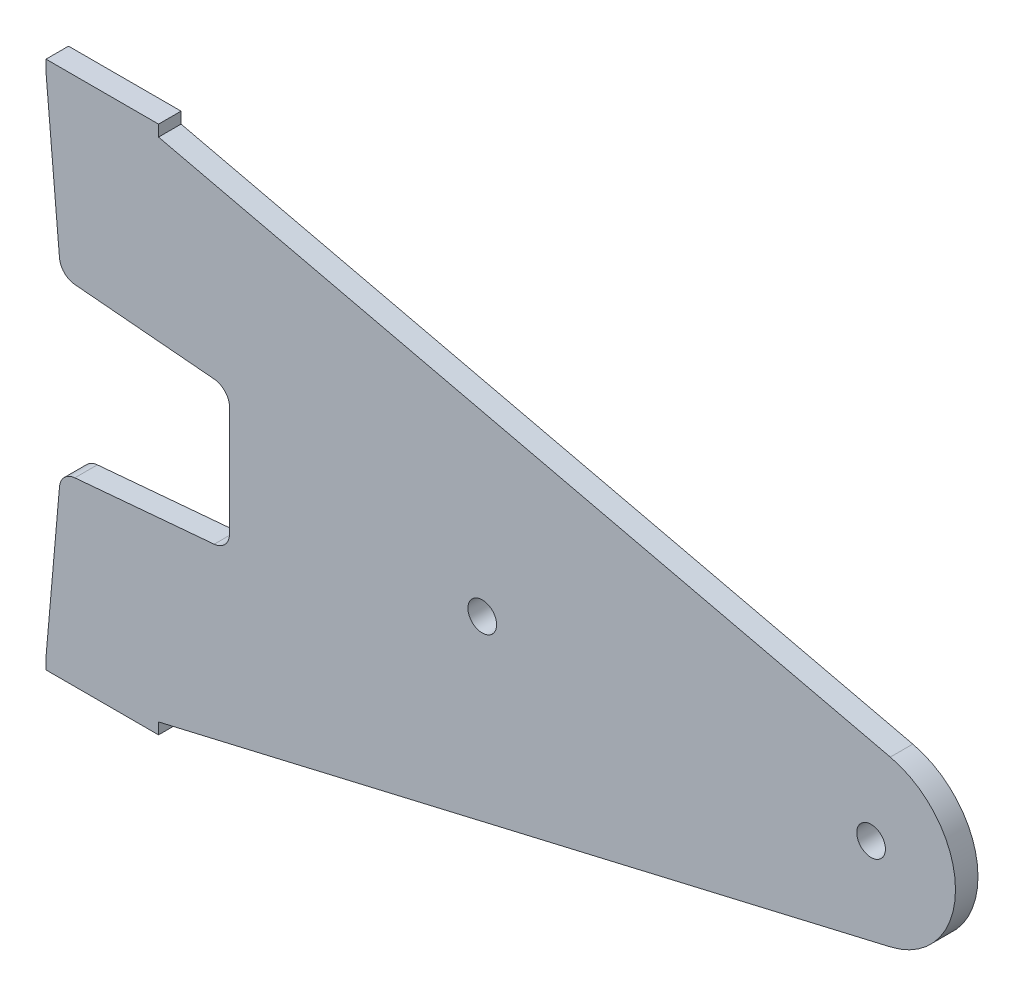
SolidWorks part; units mm, degrees
ref_plane "Front Plane" through (0, 0, 0) normal (0, 0, 1) x (1, 0, 0)
ref_plane "Top Plane" through (0, 0, 0) normal (0, 1, 0) x (1, 0, 0)
ref_plane "Right Plane" through (0, 0, 0) normal (1, 0, 0) x (0, 0, -1)
sketch "Sketch1" plane through (0, 0, 0) normal (0, 0, 1) x (1, 0, 0)
  line L0 (0, 0) -> (225, 0) construction
  line L1 (0, 0) -> (-75.9033, 0) construction
  line L2 (15, 15) -> (45, 12.375) construction
  line L3 (-45, -45) -> (45, -45) construction
  line L4 (-45, -45) -> (-45, 45) construction
  line L5 (-45, 45) -> (45, 45) construction
  line L6 (45, -45) -> (45, 45) construction
  line L7 (-45, -45) -> (45, 45) construction
  line L8 (-45, 45) -> (45, -45) construction
  line L9 (-15, -15) -> (15, -15) construction
  line L10 (-15, -15) -> (-15, 15) construction
  line L11 (-15, 15) -> (15, 15) construction
  line L12 (15, -15) -> (15, 15) construction
  line L13 (-15, -15) -> (15, 15) construction
  line L14 (-15, 15) -> (15, -15) construction
  line L15 (15, 15) -> (45, 15) construction
  line L16 (45, 45) -> (15, 15) construction
  line L17 (15, 15) -> (12.375, 45) construction
  line L18 (14.8729, 17.6) -> (12.7063, 42.3615)
  line L19 (17.6, 14.8729) -> (42.3615, 12.7063)
  line L20 (15.0923, 15.0923) -> (12.4746, 45.0087) construction
  line L21 (15.0923, 15.0923) -> (45.0087, 12.4746) construction
  line L22 (45.1, -9.7177) -> (45.1, 9.7177)
  line L23 (12.7063, 42.3615) -> (12.4746, 45.0087)
  line L24 (45.1, -45) -> (45.1, 45) construction
  line L26 (17.6, -14.8729) -> (42.3615, -12.7063)
  line L27 (14.8729, -17.6) -> (12.7063, -42.3615) construction
  line L28 (0, -45.1) -> (9.7177, -45.1) construction
  line L29 (0, 0) -> (0, 45.1) construction
  line L30 (-14.8729, 17.6) -> (-12.7063, 42.3615) construction
  line L31 (32.4746, 45) -> (162.5092, 14.6063)
  line L32 (-45, 47) -> (45, 47) construction
  line L33 (-12.7063, 42.3615) -> (-13.7896, 29.9807) construction
  line L34 (225, -45) -> (45, -45) construction
  line L35 (225, -45) -> (225, 45) construction
  line L36 (225, 45) -> (45, 45) construction
  line L37 (45, -45) -> (45, 45) construction
  line L38 (225, -45) -> (45, 45) construction
  line L39 (225, 45) -> (45, -45) construction
  line L40 (12.4746, 45.0087) -> (12.4746, 47)
  line L41 (12.4746, 47) -> (32.4746, 47)
  line L42 (32.4746, -47) -> (32.4746, -45)
  line L43 (12.4746, -47) -> (32.4746, -47)
  line L44 (14.8729, -17.6) -> (12.7063, -42.3615)
  line L45 (12.4746, -45.0087) -> (12.4746, -47)
  line L46 (12.7063, -42.3615) -> (12.4746, -45.0087)
  line L47 (32.4746, 47) -> (32.4746, 45)
  line L48 (32.4746, -45) -> (162.5092, -14.6063)
  line L49 (174.0952, 0) -> (45.1, 0) construction
  arc A0 (14.8729, 17.6) -> (17.6, 14.8729) centre (17.8615, 17.8615) ccw
  arc A1 (42.3615, 12.7063) -> (45.1, 9.7177) centre (42.1, 9.7177) cw
  arc A2 (162.5092, 14.6063) -> (162.5092, -14.6063) centre (159.0952, 0) cw
  arc A3 (42.3615, -12.7063) -> (45.1, -9.7177) centre (42.1, -9.7177) ccw
  arc A4 (14.8729, -17.6) -> (17.6, -14.8729) centre (17.8615, -17.8615) cw
  arc A5 (12.7063, -42.3615) -> (9.7177, -45.1) centre (9.7177, -42.1) cw construction
  arc A6 (-12.7063, 42.3615) -> (-9.7177, 45.1) centre (-9.7177, 42.1) cw construction
  circle A7 centre (159.0952, 0) radius 2.55
  circle A8 centre (90, 0) radius 2.55
  point P28 (135, 0)
  point P33 (45.1, 0)
  dimension "D5" = 3
  dimension "D7" = 3
  dimension "D9" = 2
  dimension "D10" = 20
  dimension "D11" = 15
  dimension "D12" = 5.1
  dimension "D13" = 90
  dimension "D1" = 90
  dimension "D2" = 0.1
  dimension "D3" = 30
  dimension "D4" = 2.625
  dimension "D8" = 180
  dimension "D6" = 0.1
extrude "Boss-Extrude1" add sketch "Sketch1" along normal blind 4
